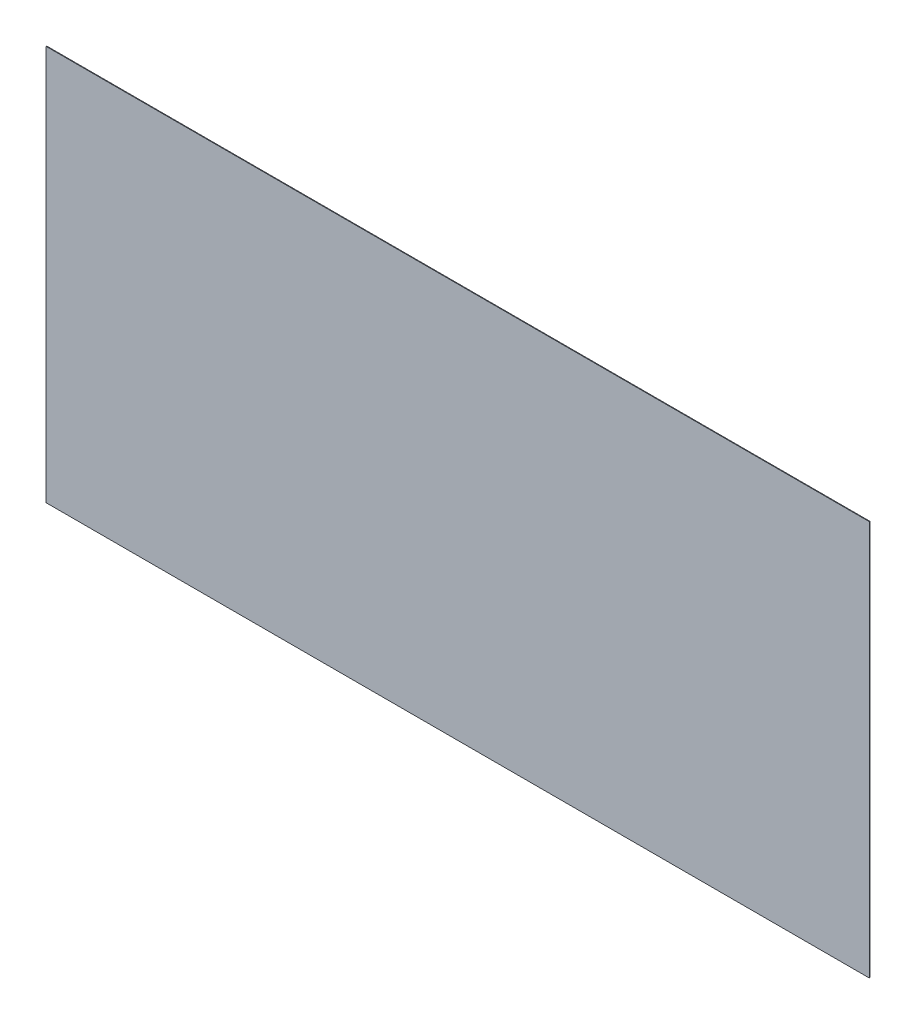
SolidWorks part; units mm, degrees
ref_plane "Alzado" through (0, 0, 0) normal (0, 0, 1) x (1, 0, 0)
ref_plane "Planta" through (0, 0, 0) normal (0, 1, 0) x (1, 0, 0)
ref_plane "Vista lateral" through (0, 0, 0) normal (1, 0, 0) x (0, 0, -1)
sketch "Croquis1" plane through (0, 0, 0) normal (0, 0, 1) x (1, 0, 0)
  line L1 (-600, 288.1) -> (600, 288.1)
  line L2 (-600, 288.1) -> (-600, -288.1)
  line L3 (-600, -288.1) -> (600, -288.1)
  line L4 (600, 288.1) -> (600, -288.1)
  line L5 (-600, 288.1) -> (600, -288.1) construction
  line L6 (-600, -288.1) -> (600, 288.1) construction
  point P0 (0, 0)
  dimension "D1" = 576.2
  dimension "D2" = 1200
extrude "Saliente-Extruir1" add sketch "Croquis1" along normal blind 0.9
